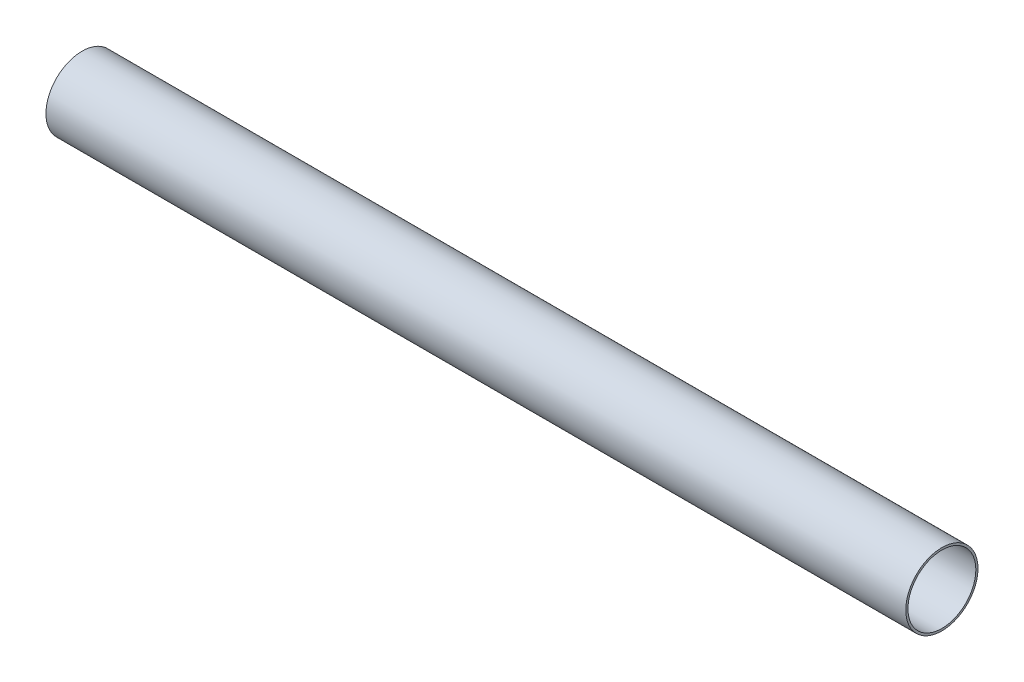
SolidWorks part; units mm, degrees
ref_plane "Alzado" through (0, 0, 0) normal (0, 0, 1) x (1, 0, 0)
ref_plane "Planta" through (0, 0, 0) normal (0, 1, 0) x (1, 0, 0)
ref_plane "Vista lateral" through (0, 0, 0) normal (1, 0, 0) x (0, 0, -1)
sketch "Croquis1" plane through (0, 0, 0) normal (1, 0, 0) x (0, 0, -1)
  circle A0 centre (0, 0) radius 84
  circle A1 centre (0, 0) radius 79
  dimension "D1" = 158
  dimension "D2" = 168
extrude "Saliente-Extruir1" add sketch "Croquis1" along normal blind 2000
